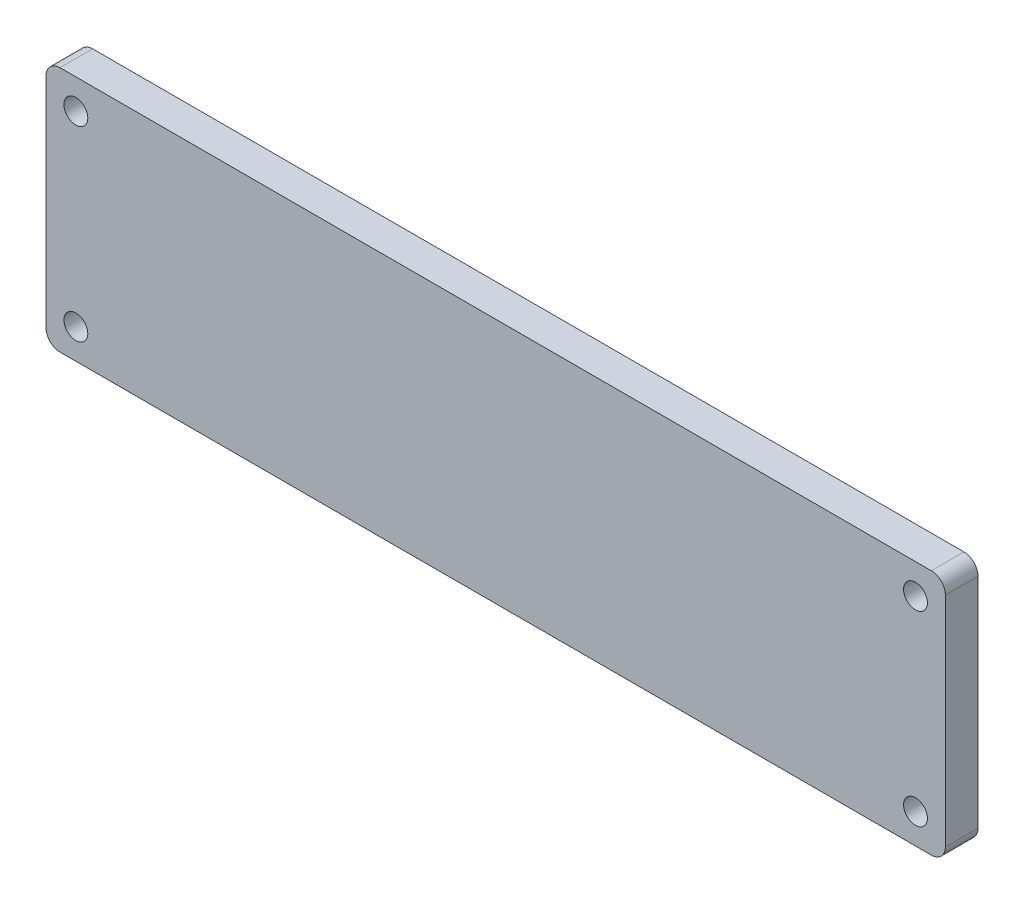
SolidWorks part; units mm, degrees
ref_plane "前视基准面" through (0, 0, 0) normal (0, 0, 1) x (1, 0, 0)
ref_plane "上视基准面" through (0, 0, 0) normal (0, 1, 0) x (1, 0, 0)
ref_plane "右视基准面" through (0, 0, 0) normal (1, 0, 0) x (0, 0, -1)
sketch "草图1" plane through (0, 0, 0) normal (0, 0, 1) x (1, 0, 0)
  line L0 (0, 13.2) -> (0, -13.2) construction
  line L1 (-46.7, 13.2) -> (46.7, 13.2)
  line L2 (-48.2, 11.7) -> (-48.2, -11.7)
  line L3 (-46.7, -13.2) -> (46.7, -13.2)
  line L4 (48.2, 11.7) -> (48.2, -11.7)
  line L5 (-48.2, 0) -> (48.2, 0) construction
  arc A0 (48.2, 11.7) -> (46.7, 13.2) centre (46.7, 11.7) ccw
  arc A1 (48.2, -11.7) -> (46.7, -13.2) centre (46.7, -11.7) cw
  arc A2 (-46.7, -13.2) -> (-48.2, -11.7) centre (-46.7, -11.7) cw
  arc A3 (-48.2, 11.7) -> (-46.7, 13.2) centre (-46.7, 11.7) cw
  circle A4 centre (-45, 10) radius 1.28
  circle A5 centre (45, 10) radius 1.28
  circle A6 centre (45, -10) radius 1.28
  circle A7 centre (-45, -10) radius 1.28
  point P0 (0, 0)
  point P8 (48.2, 13.2)
  point P13 (-48.2, -13.2)
  point P16 (-48.2, 13.2)
  point P34 (0, 0)
  dimension "D3" = 1.5
  dimension "D4" = 2.56
  dimension "D5" = 20
  dimension "D6" = 90
  dimension "D1" = 96.4
  dimension "D2" = 26.4
extrude "凸台-拉伸1" add sketch "草图1" along normal blind 3.5
